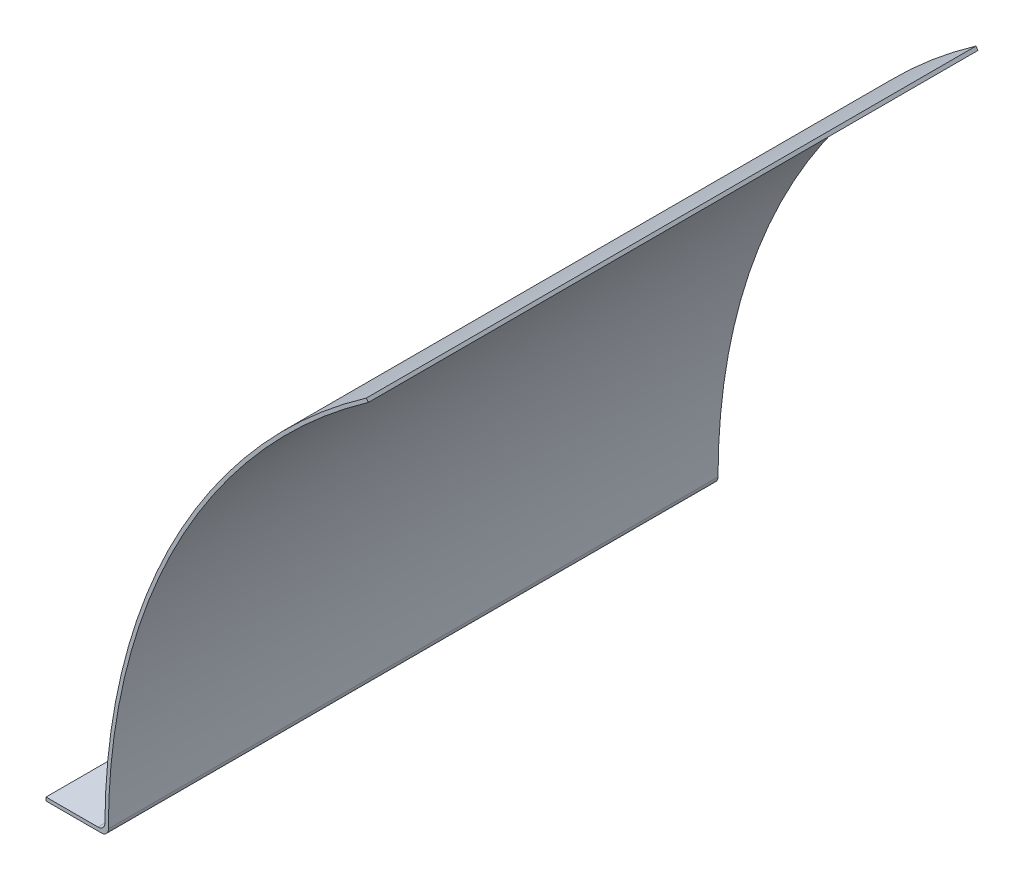
SolidWorks part; units mm, degrees
ref_plane "Front Plane" through (0, 0, 0) normal (0, 0, 1) x (1, 0, 0)
ref_plane "Top Plane" through (0, 0, 0) normal (0, 1, 0) x (1, 0, 0)
ref_plane "Right Plane" through (0, 0, 0) normal (1, 0, 0) x (0, 0, -1)
sketch "Sketch1" plane through (0, 0, 0) normal (0, 0, 1) x (1, 0, 0)
  line L0 (-279.4, 0) -> (0, 0) construction
  line L1 (0, 0) -> (-161.1678, 230.1715) construction
  line L2 (-284.1581, -1.5875) -> (-307.975, -1.5875)
  line L3 (-160.2573, 228.8711) -> (-161.1678, 230.1715)
  line L4 (18.8061, -152.4) -> (-899.1704, -152.4) construction
  line L6 (-282.575, -3.175) -> (-307.975, -3.175)
  line L7 (-307.975, -3.175) -> (-307.975, -1.5875)
  arc A0 (-280.9831, 1.5698) -> (-161.1678, 230.1715) centre (0, 0) cw
  arc A1 (-279.4, 0) -> (-160.2573, 228.8711) centre (0, 0) cw
  arc A2 (-279.4, 0) -> (-282.575, -3.175) centre (-282.575, 0) cw
  arc A3 (-280.9831, 1.5698) -> (-284.1581, -1.5875) centre (-284.1581, 1.5875) cw
  dimension "D1" = 55
  dimension "D2" = 1.5875
  dimension "D5" = 1.5875
  dimension "D7" = 3.175
  dimension "D3" = 280.9875
  dimension "D4" = 152.4
  dimension "D6" = 25.4
extrude "Boss-Extrude1" add sketch "Sketch1" along normal blind 279.4
